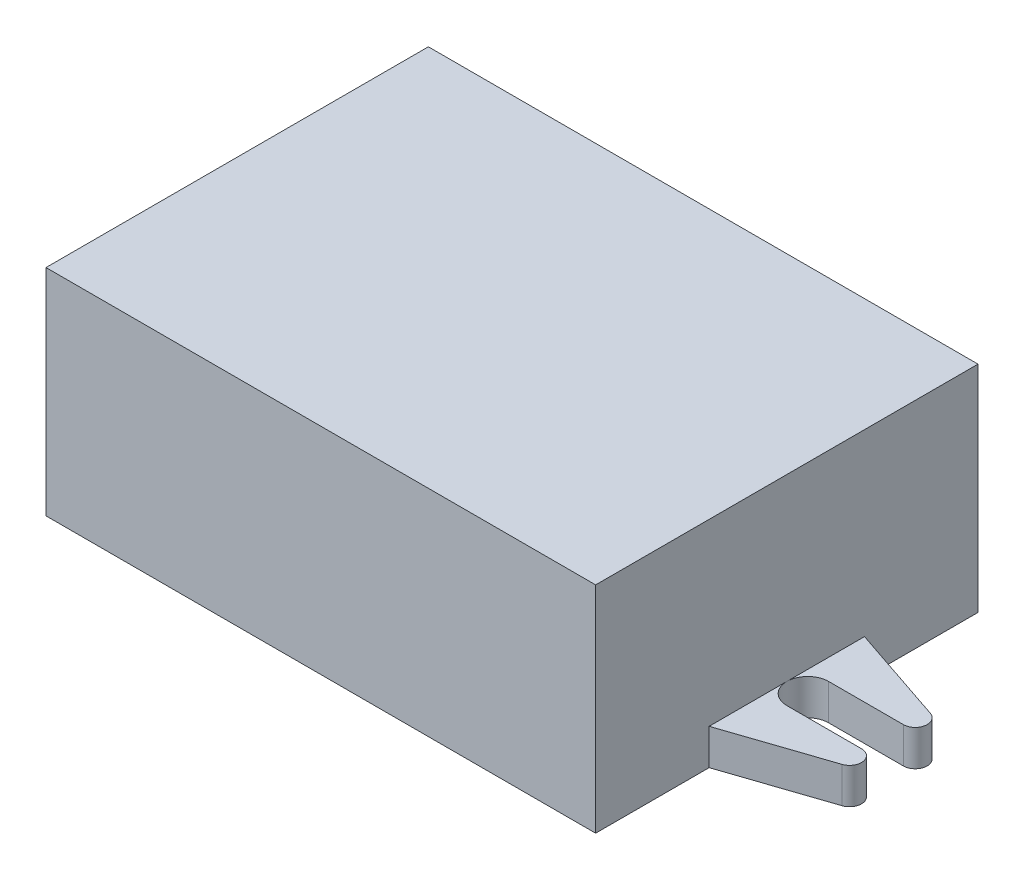
SolidWorks part; units mm, degrees
ref_plane "Front Plane" through (0, 0, 0) normal (0, 0, 1) x (1, 0, 0)
ref_plane "Top Plane" through (0, 0, 0) normal (0, 1, 0) x (1, 0, 0)
ref_plane "Right Plane" through (0, 0, 0) normal (1, 0, 0) x (0, 0, -1)
sketch "Sketch1" plane through (0, 0, 0) normal (0, 1, 0) x (1, 0, 0)
  line L1 (-23, -16) -> (23, -16)
  line L2 (-23, -16) -> (-23, 16)
  line L3 (-23, 16) -> (23, 16)
  line L4 (23, -16) -> (23, 16)
  line L5 (-23, -16) -> (23, 16) construction
  line L6 (-23, 16) -> (23, -16) construction
  point P0 (0, 0)
  dimension "D1" = 32
  dimension "D2" = 46
extrude "Boss-Extrude1" add sketch "Sketch1" along normal blind 18
sketch "Sketch2" plane through (0, 0, 0) normal (0, 1, 0) x (1, 0, 0)
  line L0 (-24.75, 1.75) -> (-31, 1.75)
  line L1 (-31.3192, 3.6977) -> (-23, 6.5)
  line L2 (-23, 16) -> (-23, -16) construction
  line L3 (-24.75, -1.75) -> (-31, -1.75)
  line L4 (-31.3192, -3.6977) -> (-23, -6.5)
  line L5 (-23, 6.5) -> (-23, -6.5)
  line L6 (0, 0) -> (0, 9.4358) construction
  line L7 (23, 6.5) -> (23, -6.5)
  line L8 (31.3192, -3.6977) -> (23, -6.5)
  line L9 (24.75, -1.75) -> (31, -1.75)
  line L10 (31.3192, 3.6977) -> (23, 6.5)
  line L11 (24.75, 1.75) -> (31, 1.75)
  arc A0 (-24.75, -1.75) -> (-24.75, 1.75) centre (-24.75, 0) ccw
  arc A1 (-31, -1.75) -> (-31.3192, -3.6977) centre (-31, -2.75) ccw
  arc A2 (-31, 1.75) -> (-31.3192, 3.6977) centre (-31, 2.75) cw
  arc A3 (31, 1.75) -> (31.3192, 3.6977) centre (31, 2.75) ccw
  arc A4 (31, -1.75) -> (31.3192, -3.6977) centre (31, -2.75) cw
  arc A5 (24.75, -1.75) -> (24.75, 1.75) centre (24.75, 0) cw
  dimension "D1" = 1
  dimension "D2" = 3.5
  dimension "D3" = 13
  dimension "D4" = 8
extrude "Boss-Extrude2" add sketch "Sketch2" along normal blind 3 contours A2 L0 A0 L5 L1 | L3 A1 L4 L5 A0 | L7 A5 L11 A3 L10 | L9 A5 L7 L8 A4
